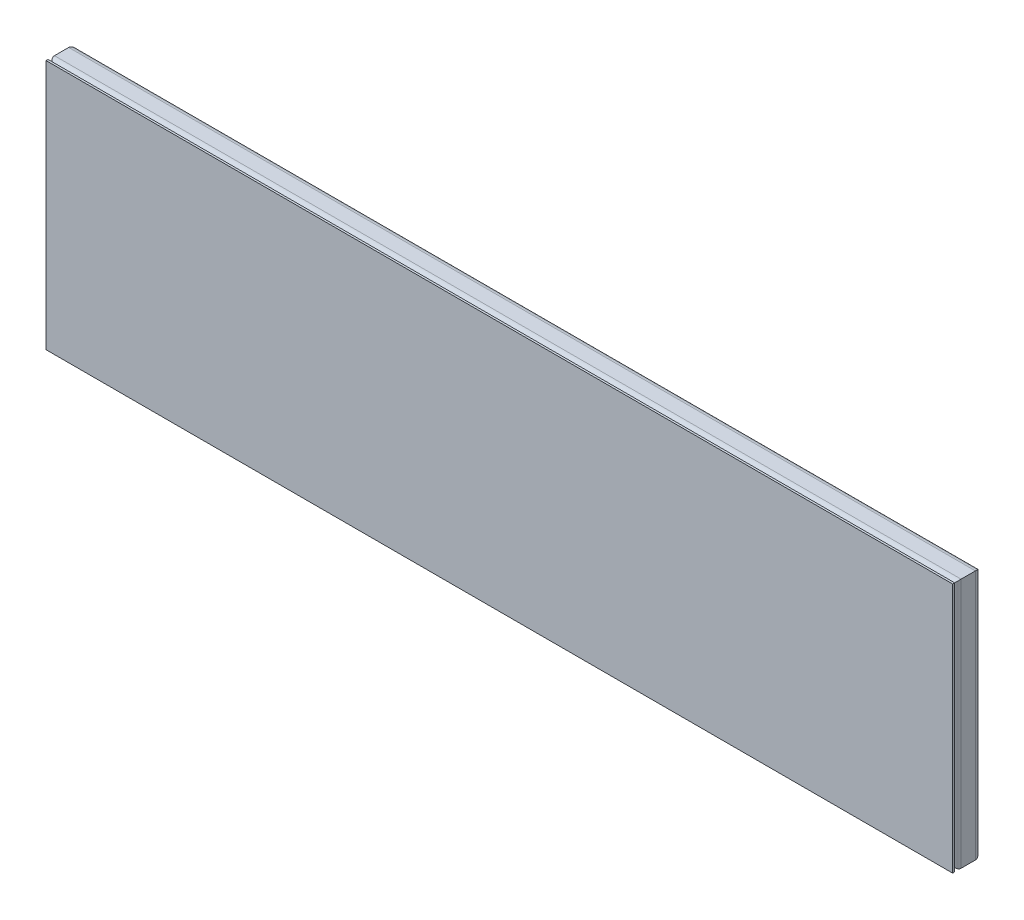
SolidWorks part; units mm, degrees
ref_plane "Alzado" through (0, 0, 0) normal (0, 0, 1) x (1, 0, 0)
ref_plane "Planta" through (0, 0, 0) normal (0, 1, 0) x (1, 0, 0)
ref_plane "Vista lateral" through (0, 0, 0) normal (1, 0, 0) x (0, 0, -1)
sketch "Croquis1" plane through (0, 0, 0) normal (0, 0, 1) x (1, 0, 0)
  line L1 (-400, 92.1) -> (400, 92.1)
  line L2 (-400, 92.1) -> (-400, -92.1)
  line L3 (-400, -92.1) -> (400, -92.1)
  line L4 (400, 92.1) -> (400, -92.1)
  line L5 (-400, 92.1) -> (400, -92.1) construction
  line L6 (-400, -92.1) -> (400, 92.1) construction
  point P0 (0, 0)
  dimension "D1" = 800
  dimension "D2" = 184.2
other "Tubo cuadrado 2 X 2 X 0.25(1)"
ref_plane "Plano1" through (-412.7, 92.1, 12.7) normal (0, -1, 0) x (1, 0, 0)
sketch "Sketch1" plane through (-412.7, 92.1, 12.7) normal (0, -1, 0) x (1, 0, 0)
  line L0 (-6.7, -9.7) -> (6.7, -9.7)
  line L1 (-9.7, -6.7) -> (-9.7, 6.7)
  line L2 (6.7, 9.7) -> (-6.7, 9.7)
  line L3 (9.7, 6.7) -> (9.7, -6.7)
  line L4 (-6.7, -12.7) -> (6.7, -12.7)
  line L5 (-12.7, -6.7) -> (-12.7, 6.7)
  line L6 (6.7, 12.7) -> (-6.7, 12.7)
  line L7 (12.7, 6.7) -> (12.7, -6.7)
  line L8 (0, 0) -> (9.7, 0) construction
  line L9 (0, 0) -> (0, 9.7) construction
  arc A0 (12.7, 6.7) -> (6.7, 12.7) centre (6.7, 6.7) ccw
  arc A1 (6.7, -12.7) -> (12.7, -6.7) centre (6.7, -6.7) ccw
  arc A2 (-12.7, -6.7) -> (-6.7, -12.7) centre (-6.7, -6.7) ccw
  arc A3 (-6.7, 12.7) -> (-12.7, 6.7) centre (-6.7, 6.7) ccw
  arc A4 (-6.7, 9.7) -> (-9.7, 6.7) centre (-6.7, 6.7) ccw
  arc A5 (9.7, 6.7) -> (6.7, 9.7) centre (6.7, 6.7) ccw
  arc A6 (6.7, -9.7) -> (9.7, -6.7) centre (6.7, -6.7) ccw
  arc A7 (-9.7, -6.7) -> (-6.7, -9.7) centre (-6.7, -6.7) ccw
  point P3 (0, 12.7)
  point P4 (12.7, 0)
  point P5 (0, -12.7)
  point P6 (-12.7, 0)
  point P7 (-12.7, 12.7)
  point P8 (-12.7, -12.7)
  point P33 (0, 0)
  point P35 (12.7, -12.7)
  point P36 (12.7, 12.7)
  point P37 (0, 0)
  dimension "D1" = 6
  dimension "Thickness" = 3
  dimension "V_leg" = 25.4
sketch "Croquis3" plane through (0, 0, 25.4) normal (0, 0, 1) x (1, 0, 0)
  line L1 (-425.4, -117.5) -> (425.4, -117.5)
  line L2 (-425.4, -117.5) -> (-425.4, 117.5)
  line L3 (-425.4, 117.5) -> (425.4, 117.5)
  line L4 (425.4, -117.5) -> (425.4, 117.5)
  line L5 (-425.4, -117.5) -> (425.4, 117.5) construction
  line L6 (-425.4, 117.5) -> (425.4, -117.5) construction
  point P0 (0, 0)
extrude "Saliente-Extruir1" add sketch "Croquis3" along normal blind 1.9 separate body
